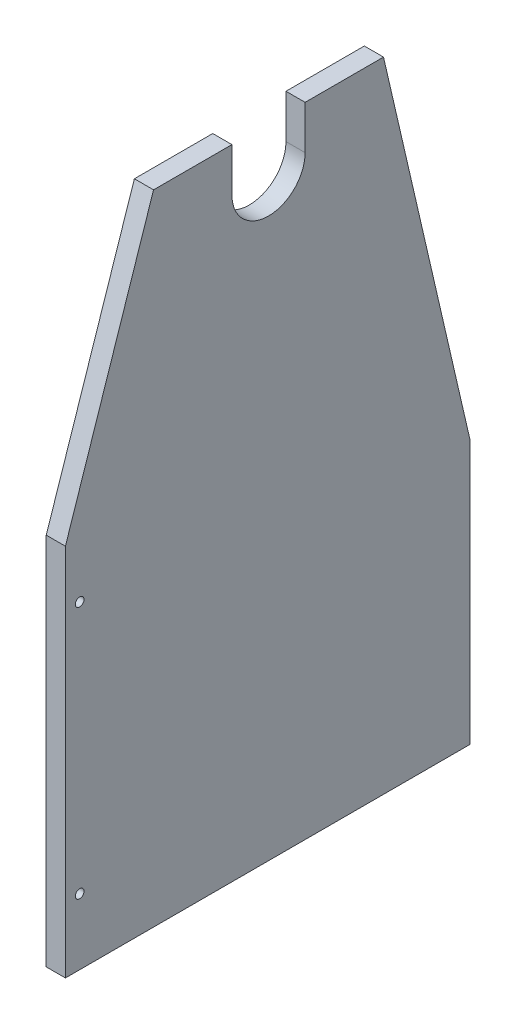
SolidWorks part; units mm, degrees
material "ParticleBoard"
ref_plane "Front Plane" through (0, 0, 0) normal (0, 0, 1) x (1, 0, 0)
ref_plane "Top Plane" through (0, 0, 0) normal (0, 1, 0) x (1, 0, 0)
ref_plane "Right Plane" through (0, 0, 0) normal (1, 0, 0) x (0, 0, -1)
sketch "Sketch1" plane through (0, 0, 0) normal (1, 0, 0) x (0, 0, -1)
  line L0 (0, 0) -> (368.3, 0)
  line L1 (368.3, 0) -> (368.3, 241.3)
  line L2 (368.3, 241.3) -> (289.7358, 581.5987)
  line L8 (80.2643, 581.5987) -> (0, 340.614)
  line L9 (0, 340.614) -> (0, 0)
  line L10 (80.2643, 581.5987) -> (289.7358, 581.5987)
  dimension "D1" = 368.3
  dimension "D2" = 340.614
  dimension "D3" = 241.3
  dimension "D4" = 349.25
  dimension "D5" = 254
  dimension "D6" = 167
extrude "Boss-Extrude1" add sketch "Sketch1" along normal blind 17.4625
sketch "RockerBoxCutout" plane through (17.4625, 0, 0) normal (1, 0, 0) x (0, 0, -1)
  line L0 (151.6626, 541.9112) -> (151.6626, 581.5987)
  line L1 (151.6626, 541.9112) -> (218.3376, 541.9112)
  line L2 (151.6626, 581.5987) -> (218.3376, 581.5987)
  line L3 (218.3376, 541.9112) -> (218.3376, 581.5987)
  line L4 (151.6626, 541.9112) -> (218.3376, 581.5987) construction
  line L5 (151.6626, 581.5987) -> (218.3376, 541.9112) construction
  line L6 (289.7358, 581.5987) -> (80.2643, 581.5987) construction
  circle A0 centre (185.0001, 541.9112) radius 33.3375
  point P1 (185.0001, 561.755)
  point P3 (185.0001, 581.5987)
  line M9 (289.7358, 581.5987) -> (80.2643, 581.5987)
  dimension "D1" = 66.675
  dimension "D2" = 39.6875
extrude "Cut-Extrude1" cut sketch "RockerBoxCutout" against normal up to surface (17.4625 mm away) contours L1 A0 | L1 A0 | A0 L3 L0 M9 up to face at (0, 290.8519, -184.4334)
sketch "Sketch2" plane through (0, 0, 0) normal (-1, 0, 0) x (0, 0, 1)
  line L0 (0, 0) -> (-368.3, 0) construction
  circle A0 centre (-13, 60) radius 3.9688
  circle A1 centre (-13, 290.1875) radius 3.9688
  dimension "D1" = 7.9375
  dimension "D2" = 7.9375
  dimension "D3" = 60
  dimension "D4" = 13
  dimension "D5" = 13
  dimension "D6" = 230.1875
extrude "Cut-Extrude2" cut sketch "Sketch2" against normal up to surface (17.4625 mm away) up to face at (17.4625, 395.8794, -184.66)
